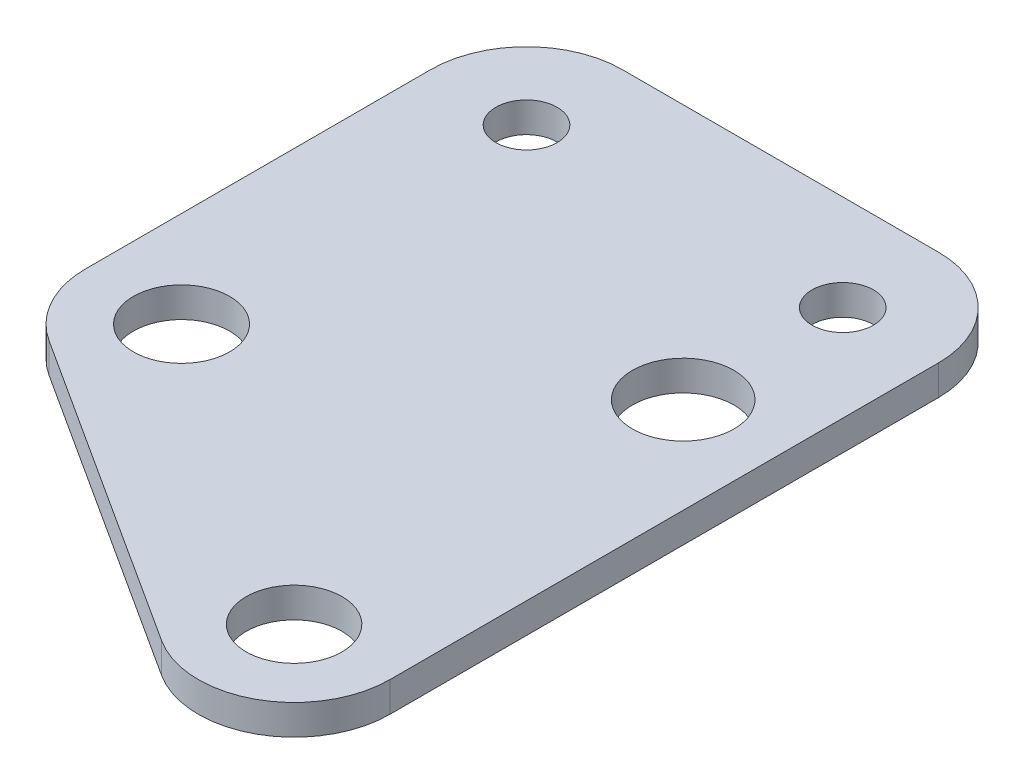
SolidWorks part; units mm, degrees
ref_plane "Front" through (0, 0, 0) normal (0, 0, 1) x (1, 0, 0)
ref_plane "Top" through (0, 0, 0) normal (0, 1, 0) x (1, 0, 0)
ref_plane "Right" through (0, 0, 0) normal (1, 0, 0) x (0, 0, -1)
sketch "Sketch1" plane through (0, 0, 0) normal (0, 1, 0) x (1, 0, 0)
  line L0 (0, 0) -> (26.5, 0)
  line L1 (26.5, 0) -> (26.5, -42.7917)
  line L2 (26.5, -42.7917) -> (0, -25.7273)
  line L3 (0, -25.7273) -> (0, 0)
  line L4 (5, -5) -> (21.5, -5) construction
  line L5 (21.5, -5) -> (21.5, -33.625) construction
  line L6 (21.5, -33.625) -> (5, -23) construction
  line L7 (5, -23) -> (5, -5) construction
  circle A0 centre (5, -23) radius 2.51
  circle A1 centre (21.5, -33.625) radius 2.5
  circle A2 centre (21.5, -5) radius 1.6
  circle A3 centre (5, -5) radius 1.6
  circle A4 centre (21.5, -13.325) radius 2.65
  dimension "D8" = 5.02
  dimension "D9" = 3.2
  dimension "D10" = 5
  dimension "D12" = 5.3
  dimension "D1" = 16.5
  dimension "D3" = 5
  dimension "D4" = 5
  dimension "D5" = 5
  dimension "D6" = 5
  dimension "D7" = 18
  dimension "D2" = 10.625
  dimension "D11" = 8.325
extrude "Boss-Extrude1" add sketch "Sketch1" along normal blind 1.57
fillet "Fillet1" radius 5 4 edges at (26.5, 0.785, 0) (0, 0.785, 0) (0, 0.785, 25.7273) (26.5, 0.785, 42.7917)
other "Move Face1" [suppressed] parameters "D1"=0.0762
equation "\"D4@Sketch1\"=\"D3@Sketch1\""
equation "\"D5@Sketch1\"=\"D3@Sketch1\""
equation "\"D6@Sketch1\"=\"D3@Sketch1\""
